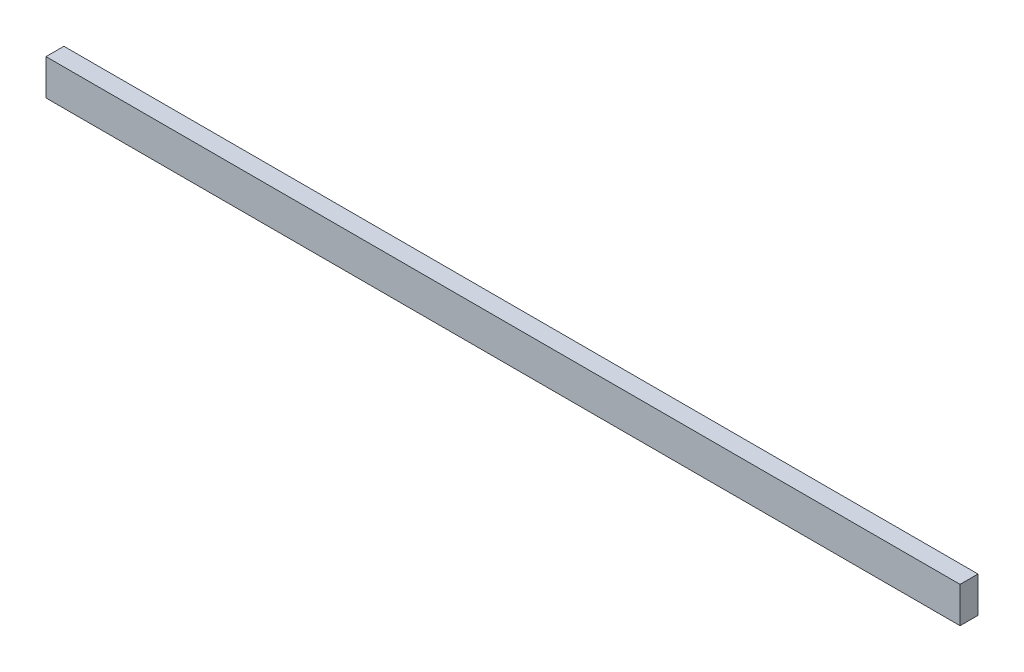
SolidWorks part; units mm, degrees
ref_plane "Plan de face" through (0, 0, 0) normal (0, 0, 1) x (1, 0, 0)
ref_plane "Plan de dessus" through (0, 0, 0) normal (0, 1, 0) x (1, 0, 0)
ref_plane "Plan de droite" through (0, 0, 0) normal (1, 0, 0) x (0, 0, -1)
sketch "Esquisse1" plane through (0, 0, 0) normal (0, 0, 1) x (1, 0, 0)
  line L1 (-25.5, -1) -> (25.5, -1)
  line L2 (-25.5, -1) -> (-25.5, 1)
  line L3 (-25.5, 1) -> (25.5, 1)
  line L4 (25.5, -1) -> (25.5, 1)
  line L5 (-25.5, -1) -> (25.5, 1) construction
  line L6 (-25.5, 1) -> (25.5, -1) construction
  point P0 (0, 0)
  dimension "D1" = 51
  dimension "D2" = 2
extrude "Boss.-Extru.1" add sketch "Esquisse1" along normal blind 1
